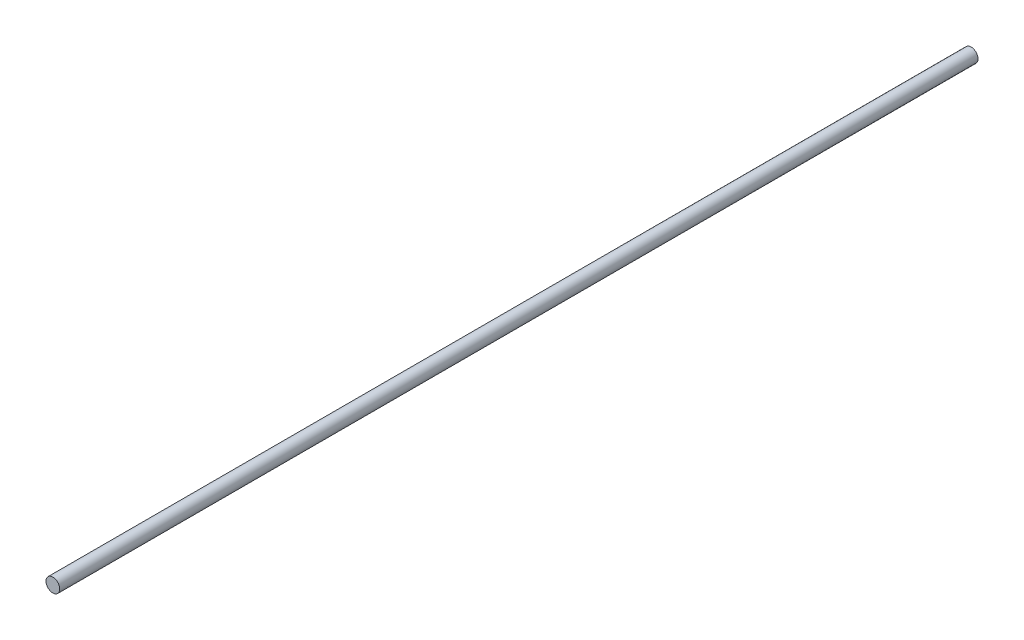
SolidWorks part; units mm, degrees
material "Stainless Steel (ferritic)"
ref_plane "Front Plane" through (0, 0, 0) normal (0, 0, 1) x (1, 0, 0)
ref_plane "Top Plane" through (0, 0, 0) normal (0, 1, 0) x (1, 0, 0)
ref_plane "Right Plane" through (0, 0, 0) normal (1, 0, 0) x (0, 0, -1)
sketch "Sketch1" plane through (0, 0, 0) normal (0, 0, 1) x (1, 0, 0)
  circle A0 centre (0, 0) radius 3
  dimension "D1" = 6
extrude "Boss-Extrude1" add sketch "Sketch1" along normal blind 400
